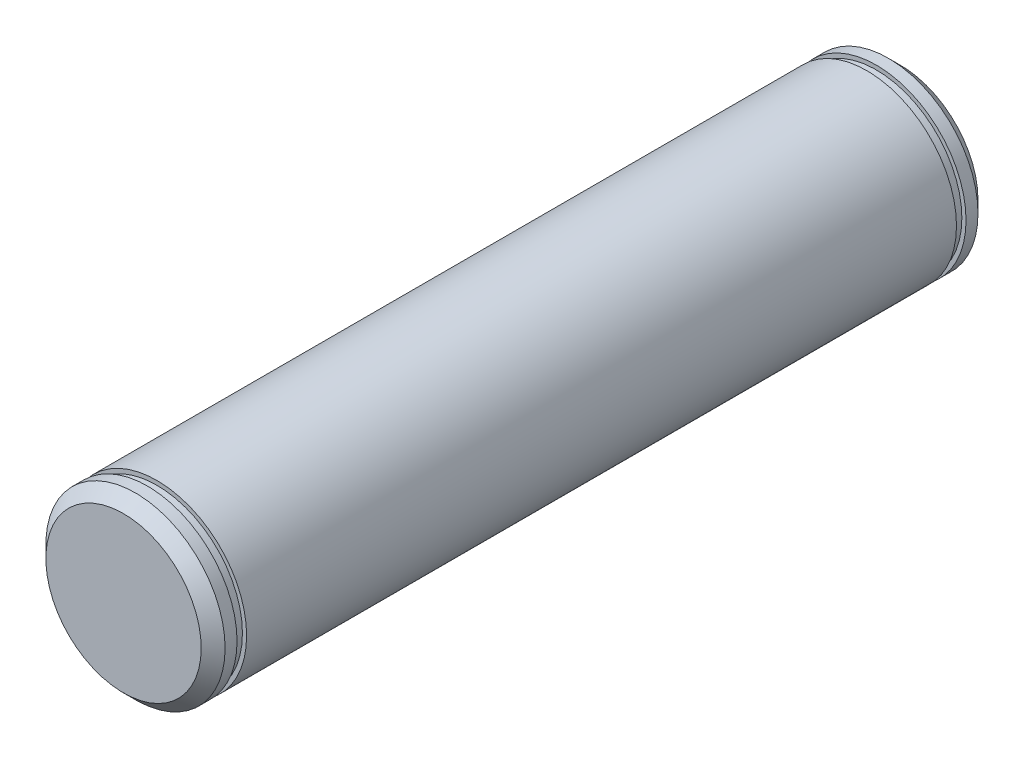
SolidWorks part; units mm, degrees
ref_plane "Front Plane" through (0, 0, 0) normal (0, 0, 1) x (1, 0, 0)
ref_plane "Top Plane" through (0, 0, 0) normal (0, 1, 0) x (1, 0, 0)
ref_plane "Right Plane" through (0, 0, 0) normal (1, 0, 0) x (0, 0, -1)
sketch "Sketch1" plane through (0, 0, 0) normal (0, 0, 1) x (1, 0, 0)
  circle A0 centre (0, 0) radius 15
  dimension "D1" = 30
extrude "Boss-Extrude1" add sketch "Sketch1" along normal blind 130 contours A0
chamfer "Chamfer1" distance 2 angle 45 2 edges at (15, 0, 130) (15, 0, 0)
sketch "Sketch2" plane through (0, 0, 0) normal (1, 0, 0) x (0, 0, -1)
  line L1 (-126, 15) -> (-124.4, 15)
  line L2 (-126, 15) -> (-126, 14.3)
  line L3 (-126, 14.3) -> (-124.4, 14.3)
  line L4 (-124.4, 15) -> (-124.4, 14.3)
  line L5 (0, -13) -> (0, 13) construction
  line L6 (-130, 0) -> (0, 0) construction
  line L7 (-130, 13) -> (-130, -13) construction
  line L8 (-5.6, 15) -> (-4, 15)
  line L13 (-5.6, 15) -> (-5.6, 14.3)
  line L14 (-5.6, 14.3) -> (-4, 14.3)
  line L15 (-4, 15) -> (-4, 14.3)
  point P6 (-126, 14.65)
  dimension "D1" = 0.7
  dimension "D2" = 1.6
  dimension "D3" = 4
  dimension "D4" = 4
  dimension "D5" = 1.6
  dimension "D6" = 0.7
  dimension "D7" = 15
revolve "Cut-Revolve1" cut sketch "Sketch2" angle 360 about L6
equation "\"D4@Sketch2\"=\"D3@Sketch2\""
equation "\"D5@Sketch2\"=\"D2@Sketch2\""
equation "\"D6@Sketch2\"=\"D1@Sketch2\""
equation "\"D7@Sketch2\"=15"
